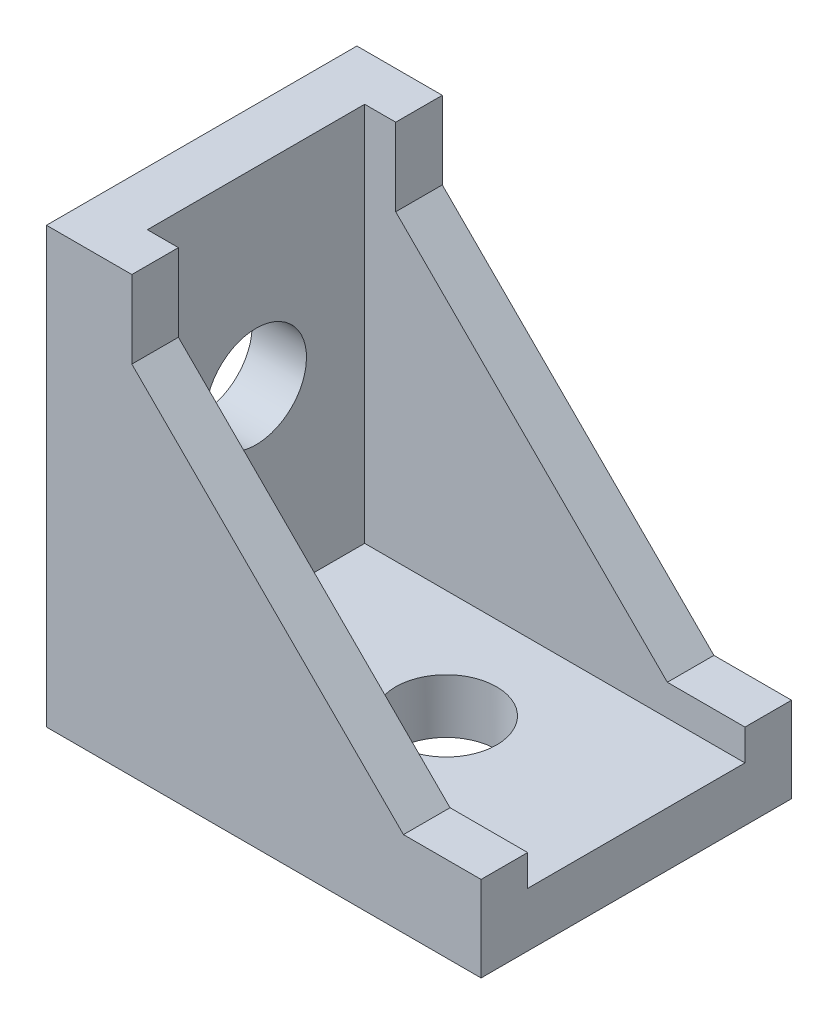
SolidWorks part; units mm, degrees
ref_plane "Front Plane" through (0, 0, 0) normal (0, 0, 1) x (1, 0, 0)
ref_plane "Top Plane" through (0, 0, 0) normal (0, 1, 0) x (1, 0, 0)
ref_plane "Right Plane" through (0, 0, 0) normal (1, 0, 0) x (0, 0, -1)
sketch "Sketch1" plane through (0, 0, 0) normal (0, 0, 1) x (1, 0, 0)
  line L0 (0, 0) -> (0, 28)
  line L1 (0, 28) -> (3.5, 28)
  line L2 (3.5, 28) -> (3.5, 3.5)
  line L3 (3.5, 3.5) -> (28, 3.5)
  line L4 (28, 3.5) -> (28, 0)
  line L5 (28, 0) -> (0, 0)
  dimension "D1" = 28
  dimension "D2" = 28
  dimension "D3" = 3.5
  dimension "D4" = 3.5
extrude "Boss-Extrude1" add sketch "Sketch1" along normal mid plane 20
sketch "Sketch2" plane through (0, 0, 10) normal (0, 0, 1) x (1, 0, 0)
  line L0 (3.5, 28) -> (5.5, 28)
  line L1 (5.5, 28) -> (5.5, 23)
  line L2 (5.5, 23) -> (23, 5.5)
  line L3 (23, 5.5) -> (28, 5.5)
  line L4 (28, 5.5) -> (28, 3.5)
  line L6 (0, 0) -> (28, 0)
  line L7 (28, 0) -> (28, 3.5)
  line L8 (28, 3.5) -> (3.5, 3.5)
  line L9 (3.5, 3.5) -> (3.5, 28)
  line L10 (3.5, 28) -> (0, 28)
  line L11 (0, 28) -> (0, 0)
  line L12 (0, 0) -> (28, 0)
  line L13 (28, 0) -> (28, 3.5)
  line L14 (28, 3.5) -> (3.5, 3.5)
  line L15 (3.5, 3.5) -> (3.5, 28)
  line L16 (3.5, 28) -> (0, 28)
  line L17 (0, 28) -> (0, 0)
  line M12 (28, 3.5) -> (3.5, 3.5)
  line M13 (3.5, 3.5) -> (3.5, 28)
  dimension "D2" = 5.5
  dimension "D3" = 5.5
  dimension "D4" = 45
  dimension "D5" = 5
  dimension "D1" = 0
extrude "Boss-Extrude2" add sketch "Sketch2" against normal blind 3 contours L4 L3 L2 L1 L0 M13 M12
mirror "Mirror1" about plane through (0, 0, 0) normal (0, 0, 1) of "Boss-Extrude2"
sketch "Sketch3" plane through (0, 3.5, 0) normal (0, 1, 0) x (1, 0, 0)
  line L0 (3.5, 7) -> (28, -7) construction
  line L4 (28, 7) -> (3.5, 7)
  line L5 (3.5, 7) -> (3.5, -7)
  line L6 (3.5, -7) -> (28, -7)
  line L7 (28, -7) -> (28, 7)
  line L8 (28, 7) -> (3.5, 7)
  line L9 (3.5, 7) -> (3.5, -7)
  line L10 (3.5, -7) -> (28, -7)
  line L11 (28, -7) -> (28, 7)
  circle A0 centre (15.75, 0) radius 3.25
  dimension "D2" = 6.5
  dimension "D1" = 0
extrude "Cut-Extrude1" cut sketch "Sketch3" against normal through all and the other way through all contours A0 L0 | L0 A0
sketch "Sketch4" plane through (3.5, 0, 0) normal (1, 0, 0) x (0, 0, -1)
  line L0 (7, 28) -> (-7, 3.5) construction
  line L4 (7, 3.5) -> (7, 28)
  line L5 (7, 28) -> (-7, 28)
  line L6 (-7, 28) -> (-7, 3.5)
  line L7 (-7, 3.5) -> (7, 3.5)
  line L8 (7, 3.5) -> (7, 28)
  line L9 (7, 28) -> (-7, 28)
  line L10 (-7, 28) -> (-7, 3.5)
  line L11 (-7, 3.5) -> (7, 3.5)
  circle A0 centre (0, 15.75) radius 3.25
  dimension "D2" = 6.5
  dimension "D1" = 0
extrude "Cut-Extrude2" cut sketch "Sketch4" against normal through all contours A0 L0 | L0 A0
